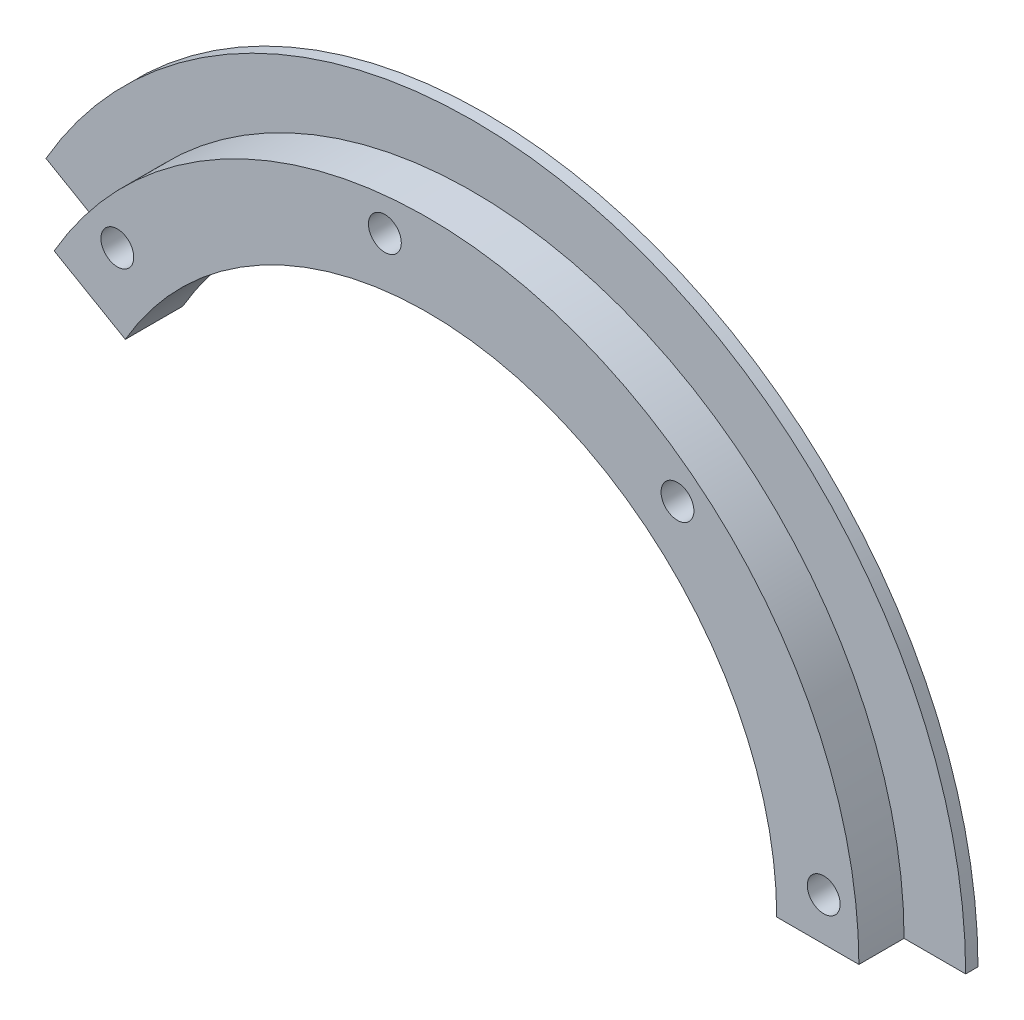
SolidWorks part; units mm, degrees
ref_plane "前视基准面" through (0, 0, 0) normal (0, 0, 1) x (1, 0, 0)
ref_plane "上视基准面" through (0, 0, 0) normal (0, 1, 0) x (1, 0, 0)
ref_plane "右视基准面" through (0, 0, 0) normal (1, 0, 0) x (0, 0, -1)
other "Configuration Table"
sketch "草图1" plane through (0, 0, 0) normal (0, 0, 1) x (1, 0, 0)
  line L0 (42.5, 0) -> (60, 0)
  line L1 (-36.8061, 21.25) -> (-51.9615, 30)
  arc A0 (60, 0) -> (-51.9615, 30) centre (0, 0) ccw
  arc A1 (42.5, 0) -> (-36.8061, 21.25) centre (0, 0) ccw
  arc A2 (48.5, 0) -> (-42.0022, 24.25) centre (0, 0) ccw construction
  circle A3 centre (48.2197, 5.207) radius 2
  circle A8 centre (-37.7783, 30.4146) radius 2
  circle A9 centre (-5.207, 48.2197) radius 2
  circle A10 centre (30.4146, 37.7783) radius 2
  circle A11 centre (-48.2197, -5.207) radius 2 [skipped]
  circle A12 centre (-30.4146, -37.7783) radius 2 [skipped]
  circle A13 centre (5.207, -48.2197) radius 2 [skipped]
  circle A14 centre (37.7783, -30.4146) radius 2 [skipped]
  point P27 (0, 0)
  dimension "D1" = 120
  dimension "D2" = 97
  dimension "D3" = 85
  dimension "D5" = 8
  dimension "D4" = 150
extrude "凸台-拉伸1" add sketch "草图1" along normal blind 7 contours A0 L1 A1 L0 | A8 | A9 | A10 | A3
sketch "草图2" plane through (0, 0, 7) normal (0, 0, 1) x (1, 0, 0)
  line L0 (52.5, 0) -> (60, 0)
  line L1 (-51.9615, 30) -> (-45.4663, 26.25)
  line L2 (-36.8061, 21.25) -> (-51.9615, 30) construction
  arc A0 (52.5, 0) -> (-45.4663, 26.25) centre (0, 0) ccw
  arc A1 (60, 0) -> (-51.9615, 30) centre (0, 0) ccw
extrude "切除-拉伸1" cut sketch "草图2" against normal blind 5.5
